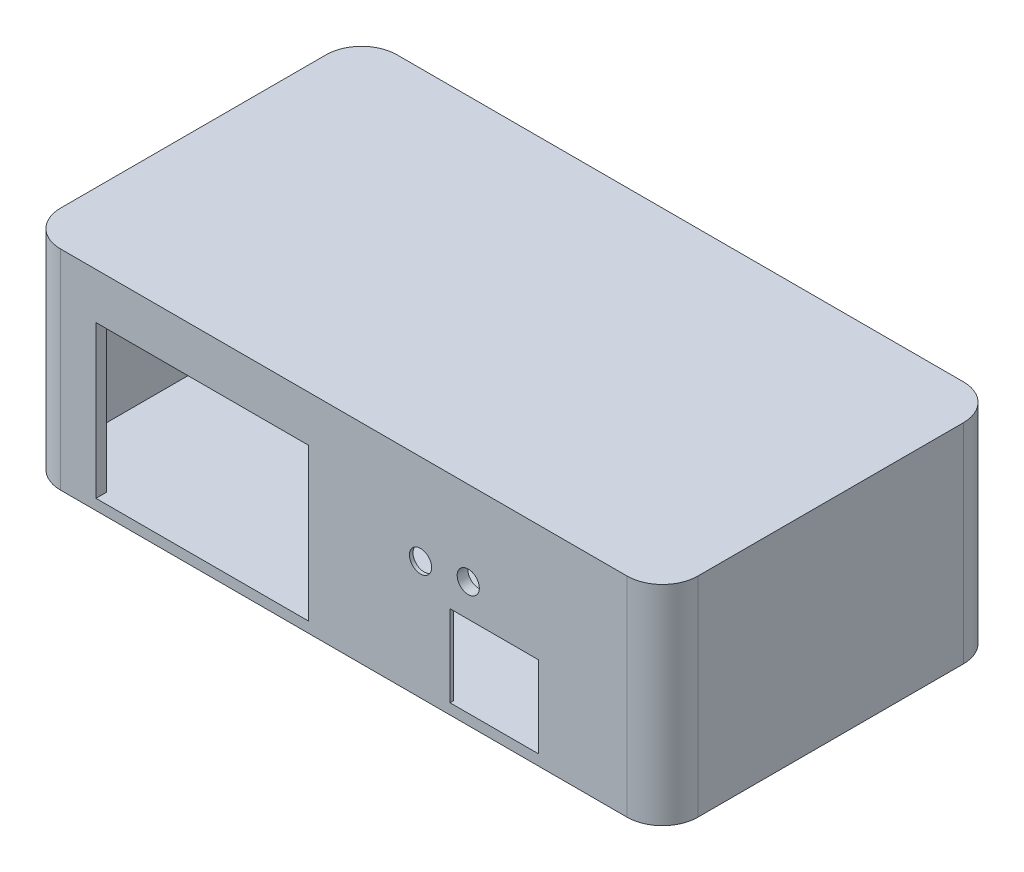
SolidWorks part; units mm, degrees
ref_plane "Front Plane" through (0, 0, 0) normal (0, 0, 1) x (1, 0, 0)
ref_plane "Top Plane" through (0, 0, 0) normal (0, 1, 0) x (1, 0, 0)
ref_plane "Right Plane" through (0, 0, 0) normal (1, 0, 0) x (0, 0, -1)
sketch "Sketch1" plane through (0, 0, 0) normal (0, 1, 0) x (1, 0, 0)
  line L1 (0, 0) -> (45.72, 0)
  line L2 (0, 0) -> (0, 24.13)
  line L3 (0, 24.13) -> (45.72, 24.13)
  line L4 (45.72, 0) -> (45.72, 24.13)
  dimension "D1" = 45.72
  dimension "D2" = 24.13
extrude "Boss-Extrude1" add sketch "Sketch1" along normal blind 12.446
shell "Shell2" thickness 0.762
sketch "Sketch2" plane through (0, 0, 0) normal (-1, 0, 0) x (0, 0, 1)
  line L1 (-23.368, 11.684) -> (-0.762, 11.684)
  line L2 (-23.368, 11.684) -> (-23.368, 0.762)
  line L3 (-23.368, 0.762) -> (-0.762, 0.762)
  line L4 (-0.762, 11.684) -> (-0.762, 0.762)
extrude "Boss-Extrude2" add sketch "Sketch2" against normal blind 0.762
fillet "Fillet1" radius 2.54 4 edges at (0, 6.223, 0) (0, 6.223, -24.13) (45.72, 6.223, 0) (45.72, 6.223, -24.13)
sketch "Sketch3" plane through (0, 0.762, 0) normal (0, 1, 0) x (1, 0, 0)
  line L3 (0.762, 0.762) -> (0.762, 12.065) construction
  line L4 (0.762, 23.368) -> (0.762, 0.762) construction
  circle A5 centre (13.462, 12.065) radius 12.065
  circle A6 centre (27.5025, 16.9671) radius 2.8067
  circle A7 centre (27.5025, 16.9671) radius 8.89
  circle A8 centre (33.3448, 6.834) radius 2.8067
  dimension "D1" = 24.13
  dimension "D3" = 17.78
  dimension "D5" = 4.9021
  dimension "D6" = 5.231
  dimension "D2" = 5.6134
  dimension "D4" = 5.6134
  dimension "D7" = 12.7
sketch "Sketch4" plane through (0, 0.762, 0) normal (0, 1, 0) x (1, 0, 0)
  line L1 (3.81, 25.4) -> (38.1, 25.4)
  line L2 (3.81, 25.4) -> (3.81, 21.59)
  line L3 (3.81, 21.59) -> (38.1, 21.59)
  line L4 (38.1, 25.4) -> (38.1, 21.59)
  line L9 (5.08, 1.27) -> (20.32, 1.27)
  line L10 (5.08, 1.27) -> (5.08, -1.27)
  line L11 (5.08, -1.27) -> (20.32, -1.27)
  line L12 (20.32, 1.27) -> (20.32, -1.27)
  dimension "D1" = 3.81
  dimension "D2" = 34.29
  dimension "D3" = 3.81
  dimension "D4" = 21.59
  dimension "D5" = 15.24
  dimension "D6" = 2.54
  dimension "D7" = 5.08
  dimension "D8" = 1.27
extrude "Cut-Extrude2" cut sketch "Sketch4" along normal up to surface (10.922 mm away) up to face at (22.86, 11.684, -12.065)
sketch "Sketch6" plane through (0, 0.762, 0) normal (0, 1, 0) x (1, 0, 0)
  line L0 (2.54, 0) -> (43.18, 0) construction
  line L1 (30.48, 0) -> (36.83, 0)
  line L2 (30.48, 0) -> (30.48, 1.27)
  line L3 (30.48, 1.27) -> (36.83, 1.27)
  line L4 (36.83, 0) -> (36.83, 1.27)
  dimension "D1" = 30.48
  dimension "D2" = 1.27
  dimension "D3" = 6.35
extrude "Cut-Extrude3" cut sketch "Sketch6" along normal up to surface (10.922 mm away)
sketch "Sketch7" plane through (0, 0, -0.762) normal (0, 0, -1) x (-1, 0, 0)
  line L1 (-30.48, 11.684) -> (-20.32, 11.684)
  line L2 (-30.48, 11.684) -> (-30.48, 0.762)
  line L3 (-30.48, 0.762) -> (-20.32, 0.762)
  line L4 (-20.32, 11.684) -> (-20.32, 0.762)
extrude "Cut-Extrude4" cut sketch "Sketch7" against normal blind 0.508
sketch "Sketch8" plane through (0, 0.762, 0) normal (0, 1, 0) x (1, 0, 0)
  circle A0 centre (13.462, 12.065) radius 3.175
  circle A1 centre (13.462, 12.065) radius 0.7937
  dimension "D1" = 6.35
  dimension "D2" = 1.5875
extrude "Boss-Extrude3" add sketch "Sketch8" along normal blind 3.81 contours A0 A1
sketch "Sketch9" plane through (0, 0.762, 0) normal (0, 1, 0) x (1, 0, 0)
  circle A0 centre (27.5025, 16.9671) radius 1.27
  circle A1 centre (27.5025, 16.9671) radius 0.381
  dimension "D1" = 2.54
  dimension "D2" = 0.762
extrude "Boss-Extrude4" add sketch "Sketch9" along normal blind 2.286
sketch "Sketch10" plane through (0, 0, 0) normal (0, -1, 0) x (1, 0, 0)
  circle A0 centre (13.462, -12.065) radius 0.7937
  circle A1 centre (27.5025, -16.9671) radius 0.381
  circle A2 centre (33.3448, -6.834) radius 0.381
  dimension "D1" = 0.762
  dimension "D2" = 0.762
  dimension "D3" = 1.5875
extrude "Cut-Extrude5" cut sketch "Sketch10" against normal up to surface (0.762 mm away)
sketch "Sketch11" plane through (0, 0, 0) normal (0, -1, 0) x (1, 0, 0)
  circle A0 centre (27.5025, -16.9671) radius 0.381
  circle A1 centre (33.3448, -6.834) radius 0.381
  dimension "D1" = 0.762
  dimension "D2" = 0.762
extrude "Boss-Extrude5" add sketch "Sketch11" against normal up to surface (0.762 mm away)
sketch "Sketch12" plane through (0, 0, 0) normal (0, 0, 1) x (1, 0, 0)
  line L2 (0, 0) -> (28.3632, 0) construction
  line L3 (2.54, 0) -> (43.18, 0) construction
  line L4 (28.3632, 0) -> (28.3632, 8.4984) construction
  circle A1 centre (28.3632, 8.4984) radius 0.7937
  dimension "D3" = 1.5875
  dimension "D1" = 28.3632
  dimension "D2" = 8.4984
extrude "Cut-Extrude6" cut sketch "Sketch12" against normal blind 0.762 contours A1
sketch "Sketch13" plane through (0, 0, -24.13) normal (0, 0, -1) x (-1, 0, 0)
  line L1 (-38.1, 11.684) -> (-3.81, 11.684)
  line L2 (-38.1, 11.684) -> (-38.1, 6.604)
  line L3 (-38.1, 6.604) -> (-3.81, 6.604)
  line L4 (-3.81, 11.684) -> (-3.81, 6.604)
  line L5 (-3.81, 0.762) -> (-3.81, 11.684) construction
  dimension "D1" = 5.08
extrude "Boss-Extrude6" add sketch "Sketch13" against normal up to surface (0.762 mm away) up to face at (2.286, 6.223, -23.368)
sketch "Sketch14" plane through (0, 0, -24.13) normal (0, 0, -1) x (-1, 0, 0)
  circle A0 centre (-28.3632, 8.4984) radius 0.7937
  dimension "D1" = 1.5875
extrude "Cut-Extrude7" cut sketch "Sketch14" against normal through all
sketch "Sketch15" plane through (0, 12.446, 0) normal (0, 1, 0) x (1, 0, 0)
  line L0 (0, 2.54) -> (0, 21.59)
  line L1 (2.54, 24.13) -> (43.18, 24.13)
  line L2 (45.72, 21.59) -> (45.72, 2.54)
  line L3 (43.18, 0) -> (2.54, 0)
  line L4 (45.72, 2.54) -> (45.72, 21.59) construction
  line L5 (43.18, 24.13) -> (2.54, 24.13) construction
  arc A0 (45.72, 21.59) -> (43.18, 24.13) centre (43.18, 21.59) ccw
  arc A1 (45.72, 2.54) -> (43.18, 0) centre (43.18, 2.54) cw
  arc A2 (2.54, 0) -> (0, 2.54) centre (2.54, 2.54) cw
  arc A3 (2.54, 24.13) -> (0, 21.59) centre (2.54, 21.59) ccw
  point P13 (0, 0)
  dimension "D1" = 2.54
extrude "Boss-Extrude7" add sketch "Sketch15" along normal blind 2.54
sketch "Sketch16" plane through (0, 11.684, 0) normal (0, -1, 0) x (1, 0, 0)
  line L9 (0.762, -0.762) -> (44.958, -0.762)
  line L10 (0.762, -0.762) -> (0.762, -23.368)
  line L11 (0.762, -23.368) -> (44.958, -23.368)
  line L12 (44.958, -0.762) -> (44.958, -23.368)
extrude "Cut-Extrude9" cut sketch "Sketch16" against normal blind 2.54
sketch "Sketch18" plane through (0, 0, 0) normal (0, 0, 1) x (1, 0, 0)
  line L0 (38.1, 6.604) -> (3.81, 6.604) construction
  line L1 (30.48, 11.684) -> (36.83, 11.684)
  line L2 (30.48, 11.684) -> (30.48, 6.604)
  line L3 (30.48, 6.604) -> (36.83, 6.604)
  line L4 (36.83, 11.684) -> (36.83, 6.604)
  line L5 (36.83, 11.684) -> (36.83, 0.762) construction
  line L6 (28.3632, 8.4984) -> (31.7861, 8.4984)
  line L7 (31.7861, 8.4984) -> (31.7861, 8.9302)
  circle A0 centre (31.7861, 8.9302) radius 0.7937
  dimension "D3" = 1.5875
  dimension "D1" = 3.4229
  dimension "D2" = 0.4318
extrude "Boss-Extrude8" add sketch "Sketch18" against normal up to surface (0.762 mm away)
sketch "Sketch19" plane through (0, 0, -24.13) normal (0, 0, -1) x (-1, 0, 0)
  circle A1 centre (-31.7861, 8.9302) radius 0.7938
  dimension "D2" = 1.5875
extrude "Cut-Extrude12" cut sketch "Sketch19" against normal blind 2.54
